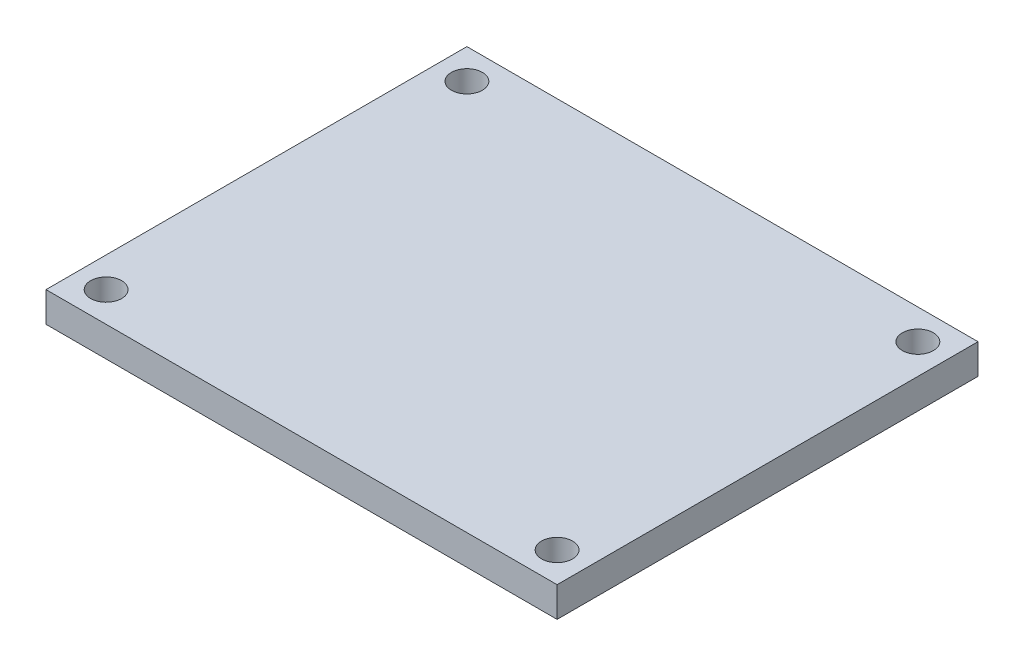
SolidWorks part; units mm, degrees
ref_plane "Front Plane" through (0, 0, 0) normal (0, 0, 1) x (1, 0, 0)
ref_plane "Top Plane" through (0, 0, 0) normal (0, 1, 0) x (1, 0, 0)
ref_plane "Right Plane" through (0, 0, 0) normal (1, 0, 0) x (0, 0, -1)
sketch "Sketch2" plane through (0, 0, 0) normal (0, 1, 0) x (1, 0, 0)
  line L0 (42.5, 70) -> (42.5, 0) construction
  line L1 (0, 0) -> (85, 0)
  line L2 (0, 0) -> (0, 70)
  line L3 (0, 70) -> (85, 70)
  line L4 (85, 0) -> (85, 70)
  line L5 (0, 35) -> (85, 35) construction
  circle A0 centre (5, 5) radius 2.58
  circle A1 centre (80, 5) radius 2.58
  circle A2 centre (80, 65) radius 2.58
  circle A3 centre (5, 65) radius 2.58
  dimension "D3" = 5.16
  dimension "D1" = 70
  dimension "D2" = 85
  dimension "D4" = 5
  dimension "D5" = 5
extrude "Boss-Extrude1" add sketch "Sketch2" along normal blind 5
